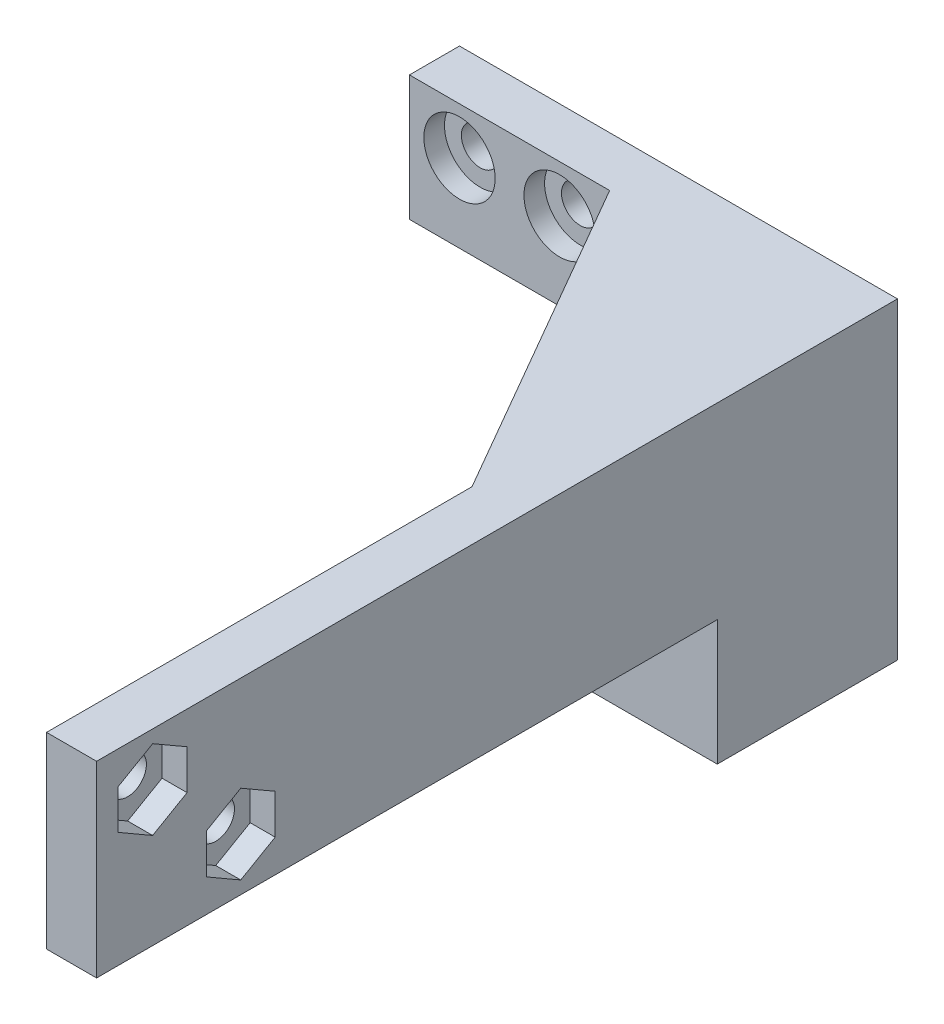
SolidWorks part; units mm, degrees
ref_plane "Alzado" through (0, 0, 0) normal (0, 0, 1) x (1, 0, 0)
ref_plane "Planta" through (0, 0, 0) normal (0, 1, 0) x (1, 0, 0)
ref_plane "Vista lateral" through (0, 0, 0) normal (1, 0, 0) x (0, 0, -1)
sketch "Croquis1" plane through (0, 0, 0) normal (0, 0, 1) x (1, 0, 0)
  line L0 (8.5228, 72.7734) -> (65.5228, 72.7734) construction
  line L1 (86, 87.7734) -> (51, 87.7734)
  line L2 (86, 87.7734) -> (86, 72.7734)
  line L3 (86, 72.7734) -> (51, 72.7734)
  line L4 (51, 87.7734) -> (51, 72.7734)
  line L5 (67, 80.2734) -> (51, 80.2734) construction
  line L6 (86, 72.7734) -> (82, 72.7734)
  line L7 (86, 72.7734) -> (86, 87.7734)
  line L8 (86, 87.7734) -> (82, 87.7734)
  line L9 (82, 72.7734) -> (82, 87.7734)
  line L10 (86, 72.7734) -> (82, 87.7734) construction
  line L11 (86, 87.7734) -> (82, 72.7734) construction
  line L12 (82, 72.7734) -> (67, 72.7734)
  line L13 (82, 72.7734) -> (82, 87.7734)
  line L14 (82, 87.7734) -> (67, 87.7734)
  line L15 (67, 72.7734) -> (67, 87.7734)
  line L16 (82, 72.7734) -> (67, 87.7734) construction
  line L17 (82, 87.7734) -> (67, 72.7734) construction
  circle A1 centre (63, 84.0234) radius 1.5
  circle A3 centre (55, 84.0234) radius 1.5
  point P10 (84, 80.2734)
  point P14 (74.5, 80.2734)
  dimension "D3" = 3
  dimension "D9" = 15
  dimension "D1" = 4
  dimension "D2" = 15
  dimension "D4" = 3.75
  dimension "D5" = 4
  dimension "D6" = 4
  dimension "D8" = 35
extrude "Saliente-Extruir1" add sketch "Croquis1" along normal blind 4
sketch "Croquis2" plane through (0, 0, 4) normal (0, 0, 1) x (1, 0, 0)
  line L0 (86, 72.7734) -> (51, 72.7734) construction
  line L1 (86, 87.7734) -> (82, 87.7734)
  line L2 (86, 87.7734) -> (86, 72.7734)
  line L3 (86, 72.7734) -> (82, 72.7734)
  line L4 (82, 87.7734) -> (82, 72.7734)
  line L5 (86, 87.7734) -> (82, 72.7734) construction
  line L6 (86, 72.7734) -> (82, 87.7734) construction
  point P4 (84, 80.2734)
  dimension "D1" = 4
extrude "Saliente-Extruir2" add sketch "Croquis2" along normal blind 60
ref_plane "Plano1" through (0, 80.2734, 0) normal (0, -1, 0) x (-1, 0, 0)
sketch "Croquis6" plane through (0, 80.2734, 0) normal (0, -1, 0) x (-1, 0, 0)
  line L0 (-82, -30) -> (-82, -4)
  line L1 (-82, -64) -> (-82, -4) construction
  line L2 (-82, -4) -> (-67, -4)
  line L3 (-82, -4) -> (-51, -4) construction
  line L4 (-67, -4) -> (-82, -30)
  line L5 (-51, -4) -> (-51, 0) construction
  point P10 (-51, -2)
  dimension "D1" = 16
  dimension "D2" = 26
extrude "Saliente-Extruir4" add sketch "Croquis6" along normal up to surface and the other way up to surface
sketch "Croquis8" plane through (0, 0, 4) normal (0, 0, 1) x (1, 0, 0)
  circle A0 centre (63, 84.0234) radius 2.85
  circle A1 centre (55, 84.0234) radius 2.85
extrude "Cortar-Extruir3" cut sketch "Croquis8" against normal blind 1.65
sketch "Croquis7" plane through (82, 0, 0) normal (-1, 0, 0) x (0, 0, 1)
  line L1 (64, 72.7734) -> (48, 72.7734) construction
  line L2 (64, 72.7734) -> (64, 87.7734) construction
  line L3 (64, 87.7734) -> (48, 87.7734) construction
  line L4 (48, 72.7734) -> (48, 87.7734) construction
  line L5 (64, 72.7734) -> (48, 87.7734) construction
  line L6 (64, 87.7734) -> (48, 72.7734) construction
  line L7 (64, 72.7734) -> (64, 87.7734) construction
  circle A2 centre (52.48, 76.9734) radius 1.5
  circle A3 centre (59.52, 83.5734) radius 1.5
  point P4 (56, 80.2734)
  dimension "D1" = 3
  dimension "D2" = 4.2
  dimension "D3" = 4.2
  dimension "D4" = 16
  dimension "D5" = 15
extrude "Cortar-Extruir2" cut sketch "Croquis7" against normal up to next
sketch "Croquis9" plane through (86, 0, 0) normal (1, 0, 0) x (0, 0, -1)
  line L1 (-55.23, 75.3857) -> (-52.48, 73.798)
  line L2 (-52.48, 73.798) -> (-49.73, 75.3857)
  line L3 (-49.73, 75.3857) -> (-49.73, 78.5611)
  line L4 (-49.73, 78.5611) -> (-52.48, 80.1488)
  line L5 (-52.48, 80.1488) -> (-55.23, 78.5611)
  line L6 (-55.23, 78.5611) -> (-55.23, 75.3857)
  line L7 (-62.27, 81.9857) -> (-59.52, 80.398)
  line L8 (-59.52, 80.398) -> (-56.77, 81.9857)
  line L9 (-56.77, 81.9857) -> (-56.77, 85.1611)
  line L10 (-56.77, 85.1611) -> (-59.52, 86.7488)
  line L11 (-59.52, 86.7488) -> (-62.27, 85.1611)
  line L12 (-62.27, 85.1611) -> (-62.27, 81.9857)
  circle A0 centre (-52.48, 76.9734) radius 2.75 construction
  circle A1 centre (-59.52, 83.5734) radius 2.75 construction
  dimension "D1" = 5.5
  dimension "D2" = 5.5
extrude "Cortar-Extruir5" cut sketch "Croquis9" against normal blind 2
sketch "Croquis10" plane through (51, 0, 0) normal (-1, 0, 0) x (0, 0, 1)
  line L1 (0, 72.7734) -> (22, 72.7734)
  line L2 (0, 72.7734) -> (0, 77.7734)
  line L3 (0, 77.7734) -> (22, 77.7734)
  line L4 (22, 72.7734) -> (22, 77.7734)
  line L5 (0, 72.7734) -> (22, 77.7734) construction
  line L6 (0, 77.7734) -> (22, 72.7734) construction
  point P4 (11, 75.2734)
  dimension "D1" = 5
  dimension "D2" = 22
extrude "Cortar-Extruir6" cut sketch "Croquis10" against normal blind 22
sketch "Croquis11" plane through (0, 72.7734, 0) normal (0, -1, 0) x (1, 0, 0)
  line L1 (73, 14.4) -> (86, 14.4)
  line L2 (73, 14.4) -> (73, 0)
  line L3 (73, 0) -> (86, 0)
  line L4 (86, 14.4) -> (86, 0)
  line L5 (73, 14.4) -> (86, 0) construction
  line L6 (73, 0) -> (86, 14.4) construction
  point P4 (79.5, 7.2)
extrude "Saliente-Extruir5" add sketch "Croquis11" along normal blind 10
